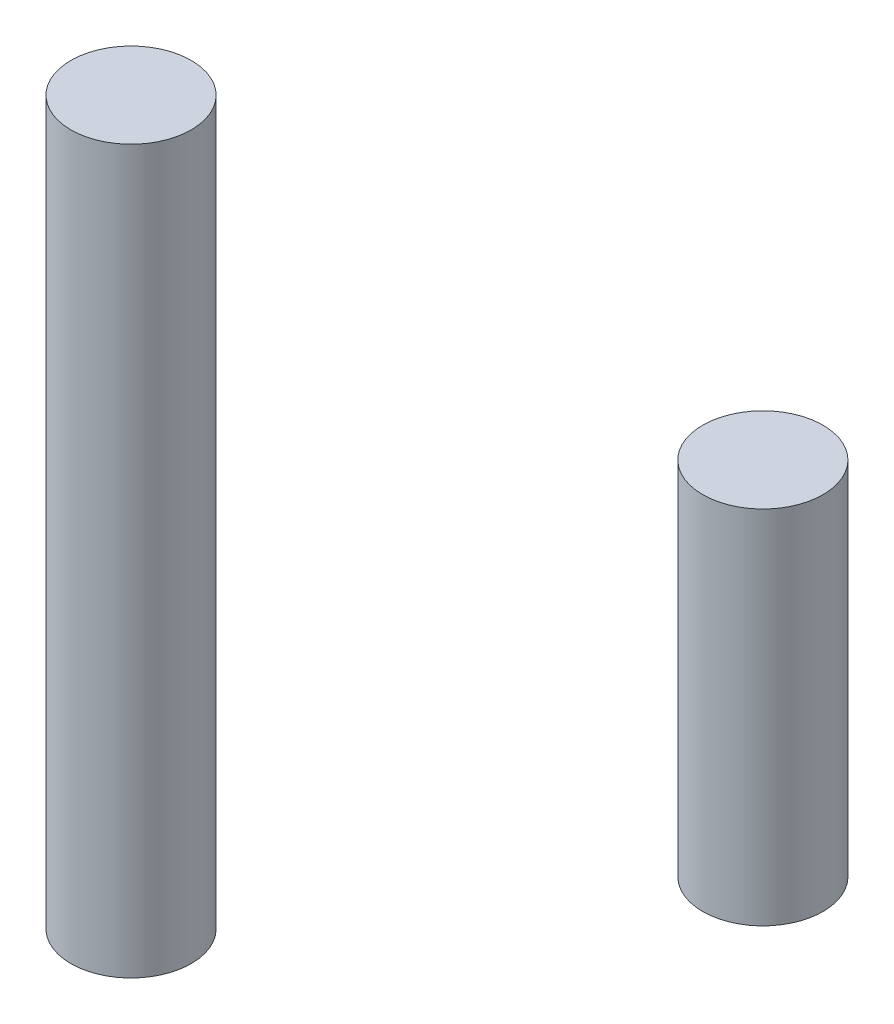
SolidWorks part; units mm, degrees
ref_plane "Front Plane" through (0, 0, 0) normal (0, 0, 1) x (1, 0, 0)
ref_plane "Top Plane" through (0, 0, 0) normal (0, 1, 0) x (1, 0, 0)
ref_plane "Right Plane" through (0, 0, 0) normal (1, 0, 0) x (0, 0, -1)
ref_plane "Plane1" through (0, -120.5, 0) normal (0, 1, 0) x (1, 0, 0)
sketch "Sketch1" plane through (0, -120.5, 0) normal (0, 1, 0) x (1, 0, 0)
  circle A0 centre (-10.5, -26) radius 2
extrude "Boss-Extrude1" add sketch "Sketch1" along normal blind 24
ref_plane "Plane2" through (0, -108.5, 0) normal (0, 1, 0) x (1, 0, 0)
sketch "Sketch2" plane through (0, -108.5, 0) normal (0, 1, 0) x (1, 0, 0)
  circle A0 centre (10.5, -26) radius 2
extrude "Boss-Extrude2" add sketch "Sketch2" along normal blind 12
